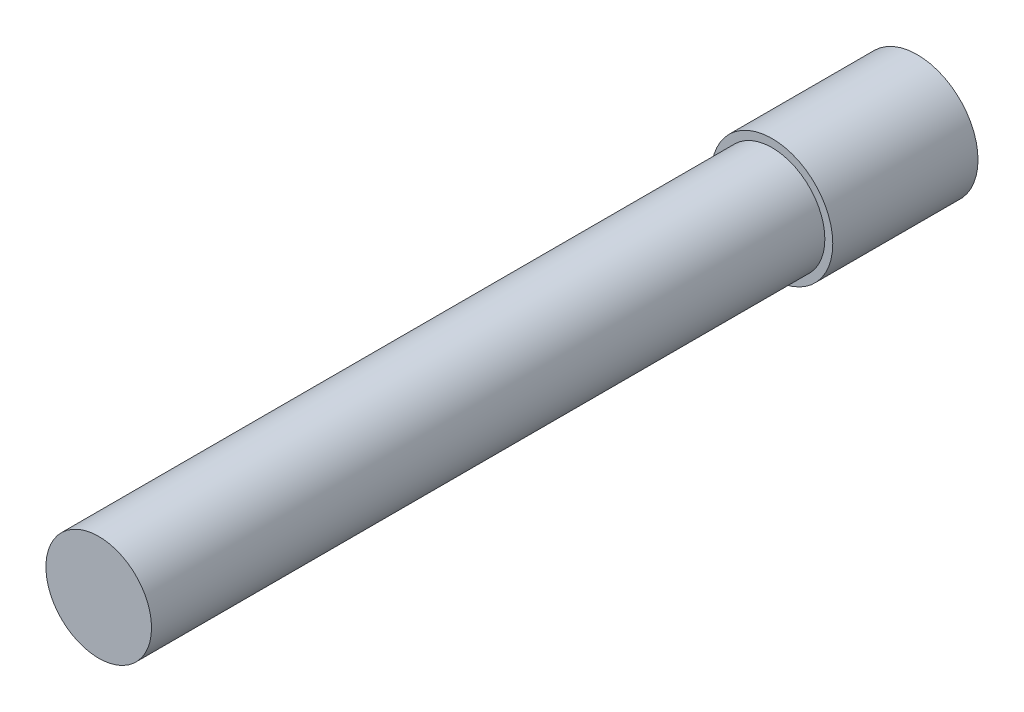
SolidWorks part; units mm, degrees
ref_plane "Plano frontal" through (0, 0, 0) normal (0, 0, 1) x (1, 0, 0)
ref_plane "Plano superior" through (0, 0, 0) normal (0, 1, 0) x (1, 0, 0)
ref_plane "Plano direito" through (0, 0, 0) normal (1, 0, 0) x (0, 0, -1)
sketch "Esboço1" plane through (0, 0, 0) normal (0, 0, 1) x (1, 0, 0)
  circle A0 centre (0, 0) radius 2.3
  dimension "D1" = 4.6
extrude "Ressalto-extrusão1" add sketch "Esboço1" along normal blind 5.5
sketch "Esboço2" plane through (0, 0, 5.5) normal (0, 0, 1) x (1, 0, 0)
  circle A0 centre (0, 0) radius 2
  dimension "D1" = 4
extrude "Ressalto-extrusão2" add sketch "Esboço2" along normal blind 25.5
cosmetic thread "Representação de rosca1" parameters "D1"=11.5, "D2"=3.22
